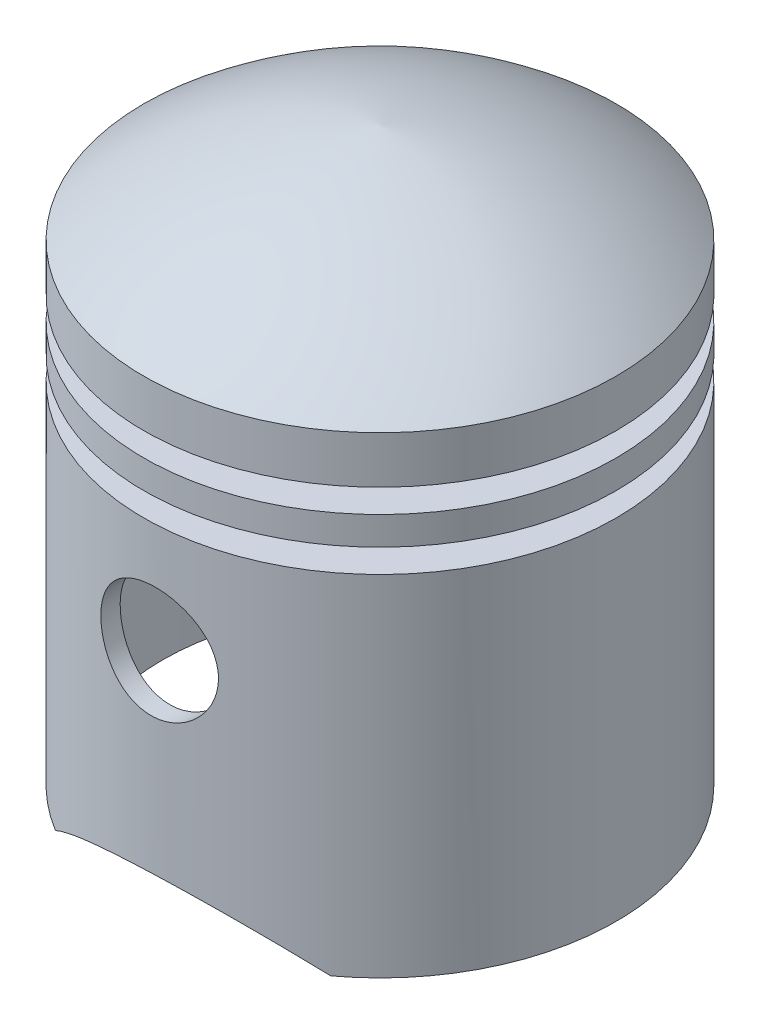
SolidWorks part; units mm, degrees
ref_plane "Front Plane" through (0, 0, 0) normal (0, 0, 1) x (1, 0, 0)
ref_plane "Top Plane" through (0, 0, 0) normal (0, 1, 0) x (1, 0, 0)
ref_plane "Right Plane" through (0, 0, 0) normal (1, 0, 0) x (0, 0, -1)
sketch "Sketch1" plane through (0, 0, 0) normal (0, 0, 1) x (1, 0, 0)
  line L0 (31.5354, 0) -> (31.5354, 37)
  line L1 (6.5354, 60.5) -> (6.5354, 0) construction
  line L2 (0, -5.6674) -> (0, 0) construction
  line L3 (0, 0) -> (31.5354, 0) construction
  line L4 (31.5354, 45) -> (26.4287, 45)
  line L5 (26.4287, 45) -> (26.4287, 42.5)
  line L6 (26.4287, 42.5) -> (31.5354, 42.5)
  line L7 (31.5354, 39.5) -> (26.4287, 39.5)
  line L8 (26.4287, 39.5) -> (26.4287, 37)
  line L9 (26.4287, 37) -> (31.5354, 37)
  line L10 (31.5354, 39.5) -> (31.5354, 42.5)
  line L11 (31.5354, 45) -> (31.5354, 50)
  line L12 (29.5354, 0) -> (29.5354, 35)
  line L13 (24.4287, 35) -> (29.5354, 35)
  line L14 (24.4287, 41) -> (24.4287, 35)
  line L15 (24.4287, 41) -> (24.4287, 41)
  line L16 (24.4287, 41) -> (24.4287, 41)
  line L17 (24.4287, 41) -> (24.4287, 41)
  line L18 (24.4287, 47) -> (24.4287, 41)
  line L19 (29.5354, 47) -> (24.4287, 47)
  line L20 (29.5354, 47) -> (29.5354, 49.0292)
  line L21 (31.5354, 0) -> (29.5354, 0)
  line L22 (6.5354, 60.5) -> (6.5354, 58.4853)
  arc A0 (31.5354, 50) -> (6.5354, 60.5) centre (0.7326, 11.6719) ccw
  arc A1 (29.5354, 49.0292) -> (6.5354, 58.4853) centre (0.7326, 11.6719) ccw
  arc A3 (29.5354, 49.0292) -> (6.2994, 58.514) centre (0.7326, 11.6719) ccw construction
  dimension "D1" = 25
  dimension "D2" = 60.5
  dimension "D3" = 50
  dimension "D4" = 5
  dimension "D5" = 2.5
  dimension "D6" = 2.5
  dimension "D7" = 3
  dimension "D8" = 2
revolve "Revolve1" add sketch "Sketch1" angle 360 about L22
sketch "Sketch2" plane through (0, 0, 0) normal (0, 0, 1) x (1, 0, 0)
  line L1 (7.4586, 0) -> (7.4586, 60.3814) construction
  line L2 (-18.4646, 0) -> (31.5354, 0) construction
  line L3 (-6.4902, 0) -> (21.4075, 0)
  arc A2 (31.5354, 50) -> (6.5354, 60.5) centre (0.7326, 11.6719) ccw construction
  circle A3 centre (7.4586, 25.2485) radius 6
  arc A4 (-6.4902, 0) -> (21.4075, 0) centre (7.4586, -17.6974) cw
  dimension "D1" = 12
extrude "Cut-Extrude2" cut sketch "Sketch2" against normal through all both and the other way through all
sketch "Sketch5" plane through (0, 0, 0) normal (0, 0, 1) x (1, 0, 0)
  circle A6 centre (7.4586, 25.2485) radius 7
  dimension "D1" = 14
extrude "Boss-Extrude12" add sketch "Sketch5" against normal through all from offset 15 separate body offset against normal yes
sketch "Sketch8" plane through (0, 0, 0) normal (0, 0, 1) x (1, 0, 0)
  circle A0 centre (7.4586, 25.2485) radius 4.4299
extrude "Cut-Extrude17" cut sketch "Sketch8" against normal offset from surface (65 mm away) 40 from offset 0 up to face at (14.4586, 25.2485, -25) offset beyond the face yes
